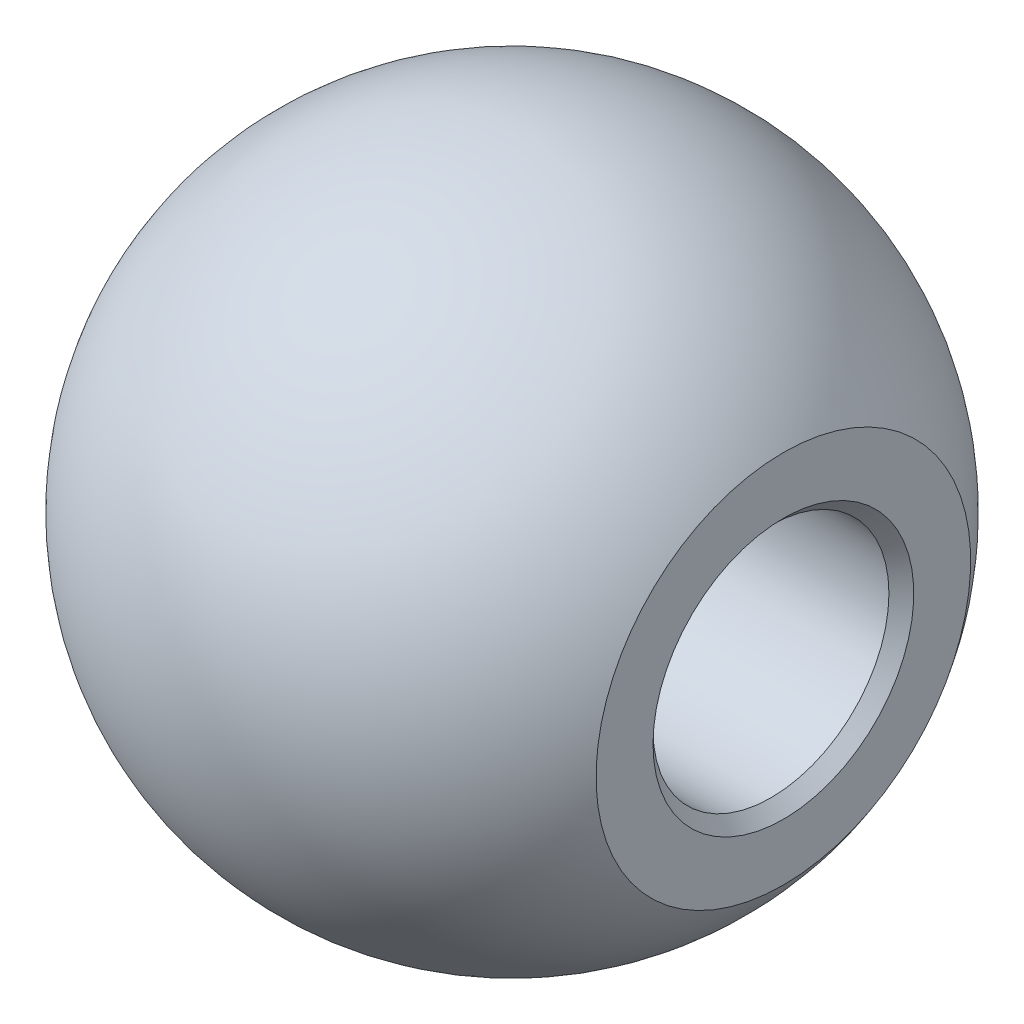
SolidWorks part; units mm, degrees
material "AISI 316 Annealed Stainless Steel Bar (SS)"
ref_plane "Front Plane" through (0, 0, 0) normal (0, 0, 1) x (1, 0, 0)
ref_plane "Top Plane" through (0, 0, 0) normal (0, 1, 0) x (1, 0, 0)
ref_plane "Right Plane" through (0, 0, 0) normal (1, 0, 0) x (0, 0, -1)
sketch "Sketch1" plane through (0, 0, 0) normal (0, 0, 1) x (1, 0, 0)
  line L0 (-6.8851, 0) -> (-3.8904, 0) construction
  line L1 (-5.5499, 3.8309) -> (-5.5499, 2.413)
  line L2 (-5.5499, 2.413) -> (5.5499, 2.413)
  line L3 (5.5499, 2.413) -> (5.5499, 3.8309)
  arc A0 (5.5499, 3.8309) -> (-5.5499, 3.8309) centre (0, 0) ccw
  dimension "Ball_Dia" = 13.4874
  dimension "B" = 4.826
  dimension "W" = 11.0998
revolve "Revolve1" add sketch "Sketch1" angle 360 about L0
chamfer "Chamfer1" distance 0.254 angle 45 2 edges at (-5.5499, 0, 2.413) (5.5499, 0, 2.413)
